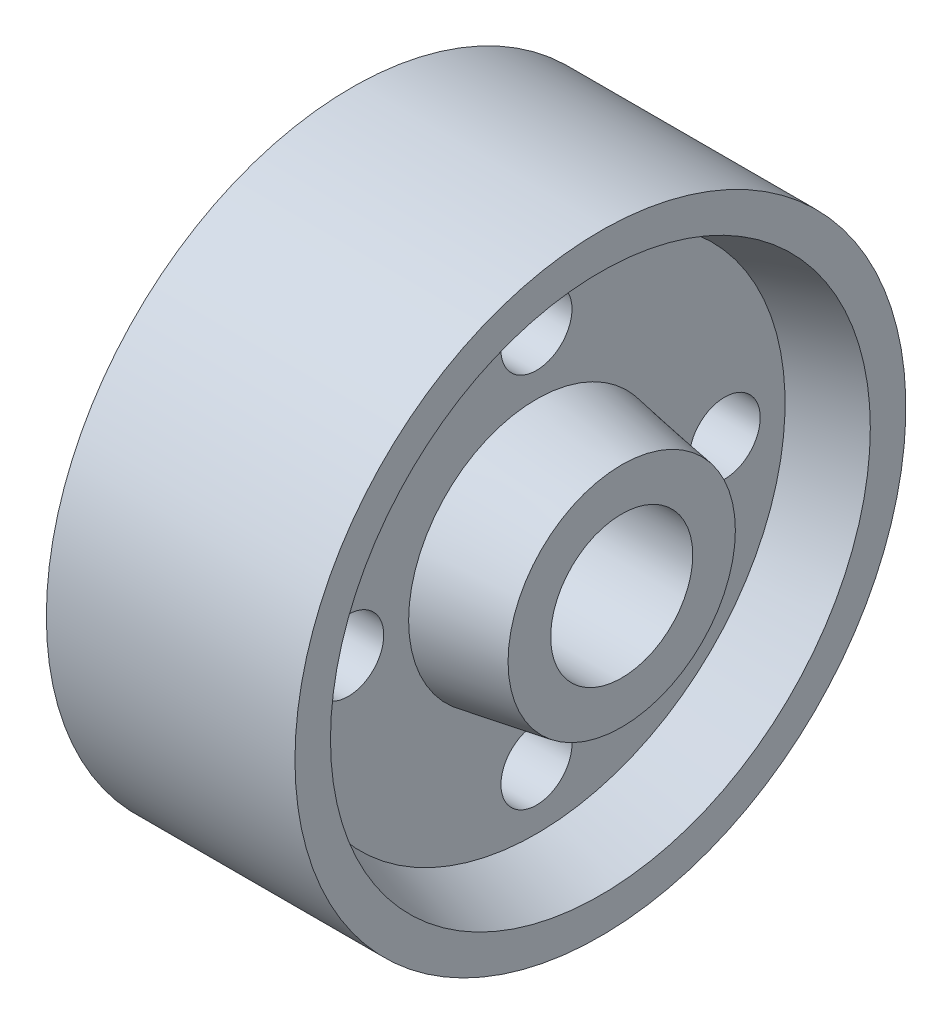
SolidWorks part; units mm, degrees
ref_plane "Front Plane" through (0, 0, 0) normal (0, 0, 1) x (1, 0, 0)
ref_plane "Top Plane" through (0, 0, 0) normal (0, 1, 0) x (1, 0, 0)
ref_plane "Right Plane" through (0, 0, 0) normal (1, 0, 0) x (0, 0, -1)
sketch "Sketch1" plane through (0, 0, 0) normal (0, 1, 0) x (1, 0, 0)
  line L0 (0, 0) -> (128.4352, 0) construction
  line L1 (0, 0) -> (0, 16)
  line L2 (0, 16) -> (12, 18)
  line L3 (12, 18) -> (12, 35)
  line L4 (12, 35) -> (3, 38)
  line L5 (3, 38) -> (3, 43)
  line L6 (3, 43) -> (38, 43)
  line L7 (20.5, 43) -> (20.5, 0) construction
  line L8 (41, 0) -> (41, 16)
  line L9 (41, 16) -> (29, 18)
  line L10 (29, 18) -> (29, 35)
  line L11 (29, 35) -> (38, 38)
  line L12 (38, 38) -> (38, 43)
  line L13 (0, 0) -> (41, 0)
  dimension "D1" = 32
  dimension "D2" = 36
  dimension "D3" = 70
  dimension "D4" = 76
  dimension "D5" = 86
  dimension "D6" = 12
  dimension "D7" = 17.5
  dimension "D8" = 20.5
revolve "Revolve1" add sketch "Sketch1" angle 360 about L13
sketch "Sketch2" plane through (41, 0, 0) normal (1, 0, 0) x (0, 0, -1)
  circle A0 centre (0, 0) radius 26.5 construction
  circle A1 centre (0, 26.5) radius 5
  circle A2 centre (26.5, 0) radius 5
  circle A3 centre (0, -26.5) radius 5
  circle A4 centre (-26.5, 0) radius 5
  point P5 (0, 0)
  point P14 (0, 0)
  dimension "D1" = 53
  dimension "D2" = 10
  dimension "D3" = 4
extrude "Cut-Extrude2" cut sketch "Sketch2" against normal through all contours A1 | A4 | A3 | A2
sketch "Sketch3" plane through (41, 0, 0) normal (1, 0, 0) x (0, 0, -1)
  circle A0 centre (0, 0) radius 10
  dimension "D1" = 20
extrude "Cut-Extrude3" cut sketch "Sketch3" against normal through all contours A0
